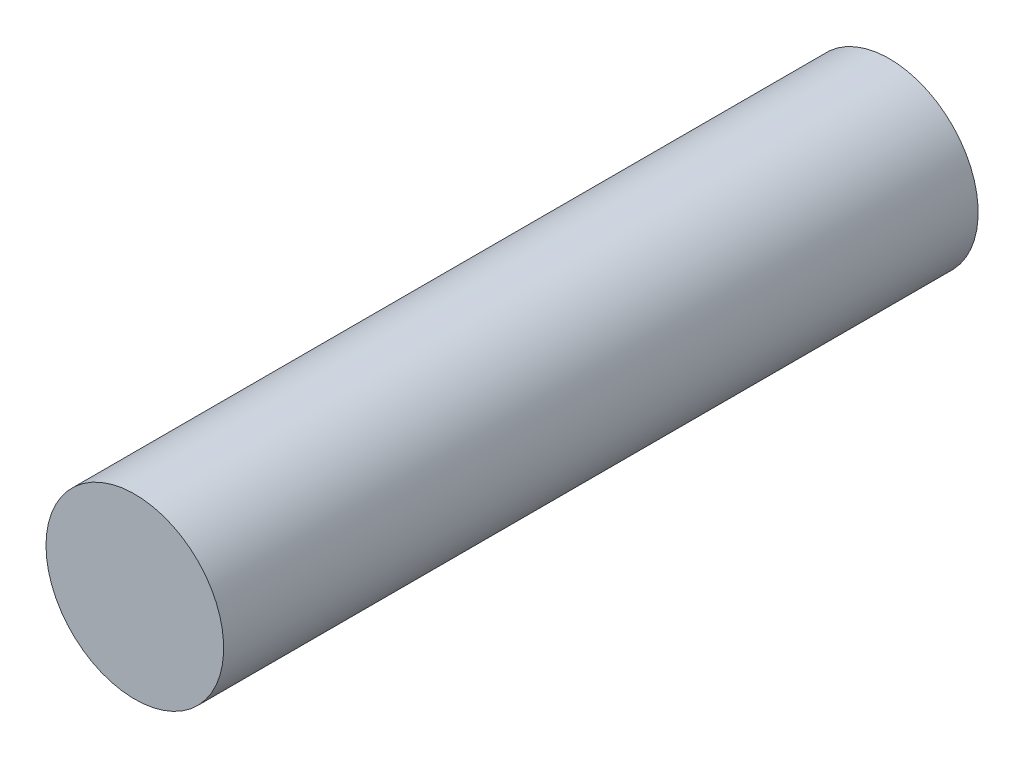
SolidWorks part; units mm, degrees
ref_plane "Plan de face" through (0, 0, 0) normal (0, 0, 1) x (1, 0, 0)
ref_plane "Plan de dessus" through (0, 0, 0) normal (0, 1, 0) x (1, 0, 0)
ref_plane "Plan de droite" through (0, 0, 0) normal (1, 0, 0) x (0, 0, -1)
sketch "Esquisse1" plane through (0, 0, 0) normal (0, 0, 1) x (1, 0, 0)
  circle A0 centre (0, 0) radius 3.25
extrude "Extrusion1" add sketch "Esquisse1" along normal blind 27.6
